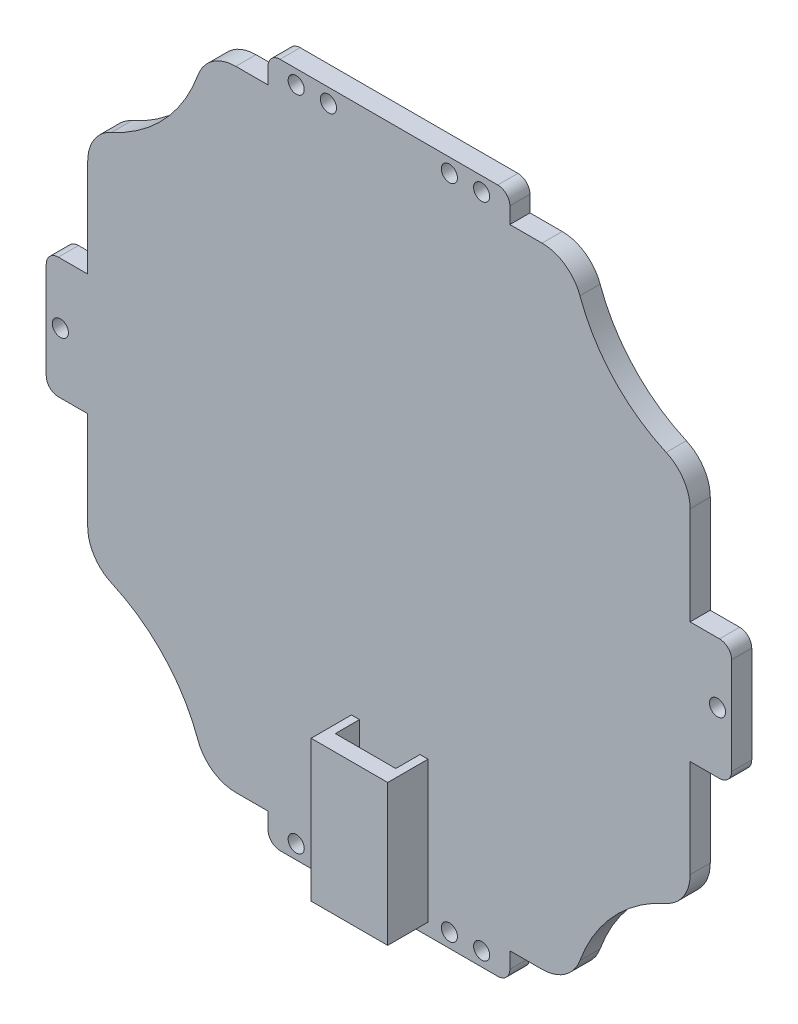
SolidWorks part; units mm, degrees
ref_plane "Front Plane" through (0, 0, 0) normal (0, 0, 1) x (1, 0, 0)
ref_plane "Top Plane" through (0, 0, 0) normal (0, 1, 0) x (1, 0, 0)
ref_plane "Right Plane" through (0, 0, 0) normal (1, 0, 0) x (0, 0, -1)
sketch "Sketch1" plane through (0, 0, 0) normal (0, 0, 1) x (1, 0, 0)
  line L0 (82, 15) -> (74.7088, 15)
  line L1 (-27, -85) -> (27, -85)
  line L2 (-85, -12) -> (-85, 12)
  line L3 (-27, 85) -> (27, 85)
  line L4 (85, -12) -> (85, 12)
  line L5 (30, 82) -> (30, 78)
  line L6 (-85, 85) -> (85, -85) construction
  line L7 (-82, 15) -> (-74.7088, 15)
  line L8 (74.7088, -15) -> (82, -15)
  line L9 (74.7088, 15) -> (74.7088, 39.3024)
  line L10 (74.7088, -15) -> (74.7088, -39.3024)
  line L11 (-74.7088, -15) -> (-82, -15)
  line L12 (-74.7088, 15) -> (-74.7088, 39.3024)
  line L13 (-74.7088, -15) -> (-74.7088, -39.3024)
  line L14 (-30, 82) -> (-30, 78)
  line L15 (30, 78) -> (37.9787, 78)
  line L16 (-30, 78) -> (-37.9787, 78)
  line L17 (30, -78) -> (37.9787, -78)
  line L18 (-30, -82) -> (-30, -78)
  line L19 (30, -82) -> (30, -78)
  line L20 (-30, -78) -> (-37.9787, -78)
  arc A0 (47.383, 71.4) -> (68.7671, 48.4419) centre (85, 85) ccw
  arc A1 (68.7671, -48.4419) -> (47.383, -71.4) centre (85, -85) ccw
  arc A2 (-47.383, -71.4) -> (-68.7671, -48.4419) centre (-85, -85) ccw
  arc A3 (-68.7671, 48.4419) -> (-47.383, 71.4) centre (-85, 85) ccw
  arc A4 (-82, -15) -> (-85, -12) centre (-82, -12) cw
  arc A5 (-85, 12) -> (-82, 15) centre (-82, 12) cw
  arc A6 (-30, -82) -> (-27, -85) centre (-27, -82) ccw
  arc A7 (27, -85) -> (30, -82) centre (27, -82) ccw
  arc A8 (85, -12) -> (82, -15) centre (82, -12) cw
  arc A9 (85, 12) -> (82, 15) centre (82, 12) ccw
  arc A10 (30, 82) -> (27, 85) centre (27, 82) ccw
  arc A11 (-27, 85) -> (-30, 82) centre (-27, 82) ccw
  arc A12 (-37.9787, 78) -> (-47.383, 71.4) centre (-37.9787, 68) ccw
  arc A13 (-68.7671, 48.4419) -> (-74.7088, 39.3024) centre (-64.7088, 39.3024) ccw
  arc A14 (-68.7671, -48.4419) -> (-74.7088, -39.3024) centre (-64.7088, -39.3024) cw
  arc A15 (-37.9787, -78) -> (-47.383, -71.4) centre (-37.9787, -68) cw
  arc A16 (37.9787, -78) -> (47.383, -71.4) centre (37.9787, -68) ccw
  arc A17 (74.7088, -39.3024) -> (68.7671, -48.4419) centre (64.7088, -39.3024) cw
  arc A18 (74.7088, 39.3024) -> (68.7671, 48.4419) centre (64.7088, 39.3024) ccw
  arc A19 (47.383, 71.4) -> (37.9787, 78) centre (37.9787, 68) ccw
  point P0 (0, 0)
  point P6 (-78.3544, -15)
  dimension "D1" = 40
  dimension "D11" = 3
  dimension "D12" = 10
  dimension "D16" = 170
  dimension "D19" = 55
  dimension "D23" = 24.3024
  dimension "D2" = 170
  dimension "D3" = 149.4177
  dimension "D4" = 149.4177
  dimension "D5" = 70
  dimension "D6" = 30
  dimension "D7" = 55
  dimension "D8" = 55
  dimension "D9" = 60
  dimension "D10" = 159.7088
  dimension "D13" = 85
  dimension "D14" = 24
  dimension "D15" = 170
  dimension "D17" = 85
  dimension "D18" = 4
  dimension "D20" = 7
  dimension "D21" = 7
  dimension "D22" = 7
  dimension "D24" = 7.2912
extrude "Boss-Extrude1" add sketch "Sketch1" along normal blind 5
sketch "Sketch2" plane through (0, 0, 0) normal (0, 0, -1) x (-1, 0, 0)
  line L0 (85, 12) -> (85, -12) construction
  line L1 (82, -15) -> (74.7088, -15) construction
  line L2 (-85, -12) -> (-85, 12) construction
  line L3 (30, 82) -> (30, 78) construction
  line L4 (-27, 85) -> (27, 85) construction
  line L5 (-30, 78) -> (-30, 82) construction
  line L6 (-82, 15) -> (-74.7088, 15) construction
  line L7 (30, -78) -> (30, -82) construction
  line L8 (-30, -82) -> (-30, -78) construction
  line L9 (27, -85) -> (-27, -85) construction
  circle A0 centre (81.5, 0) radius 2
  circle A1 centre (-81.5, 0) radius 2
  circle A2 centre (-23, 81.5) radius 2
  circle A3 centre (15, 81.5) radius 2
  circle A4 centre (23, 81.5) radius 2
  circle A5 centre (-15, 81.5) radius 2
  circle A6 centre (-23, -81.5) radius 2
  circle A7 centre (-15, -81.5) radius 2
  circle A8 centre (15, -81.5) radius 2
  circle A9 centre (23, -81.5) radius 2
  dimension "D1" = 4
  dimension "D4" = 4
  dimension "D5" = 4
  dimension "D6" = 4
  dimension "D7" = 4
  dimension "D16" = 4
  dimension "D19" = 4
  dimension "D20" = 4
  dimension "D21" = 4
  dimension "D22" = 4
  dimension "D2" = 3.5
  dimension "D3" = 15
  dimension "D8" = 7
  dimension "D9" = 15
  dimension "D10" = 3.5
  dimension "D11" = 3.5
  dimension "D12" = 15
  dimension "D13" = 7
  dimension "D14" = 3.5
  dimension "D15" = 3.5
  dimension "D17" = 3.5
  dimension "D18" = 15
  dimension "D23" = 7
  dimension "D24" = 15
  dimension "D25" = 7
  dimension "D26" = 15
  dimension "D27" = 3.5
  dimension "D28" = 3.5
  dimension "D29" = 3.5
  dimension "D30" = 3.5
extrude "Cut-Extrude1" cut sketch "Sketch2" against normal blind 5
sketch "Sketch3" plane through (0, 0, 0) normal (0, 0, -1) x (-1, 0, 0)
  line L12 (-30, -70) -> (-45, -44.0192)
  line L13 (30, -70) -> (-30, -70)
  line L14 (45, -44.0192) -> (30, -70)
  line L15 (-45, -44.0192) -> (45, -44.0192)
  line L16 (65, 45) -> (-65, 45)
  line L17 (45, 10.359) -> (65, 45)
  line L18 (-45, 10.359) -> (45, 10.359)
  line L19 (-65, 45) -> (-45, 10.359)
extrude "Cut-Extrude2" cut sketch "Sketch3" against normal blind 3
sketch "Sketch4" plane through (0, 0, 5) normal (0, 0, 1) x (1, 0, 0)
  line L0 (-27, -85) -> (27, -85) construction
  line L1 (-9.3, -47) -> (9.7, -47)
  line L2 (-9.3, -47) -> (-9.3, -82)
  line L3 (-9.3, -82) -> (9.7, -82)
  line L4 (9.7, -47) -> (9.7, -82)
  line L5 (-85, 12) -> (-85, -12) construction
  dimension "D1" = 19
  dimension "D2" = 35
  dimension "D3" = 3
  dimension "D4" = 75.7
extrude "Boss-Extrude2" add sketch "Sketch4" along normal blind 10
sketch "Sketch6" plane through (0, -82, 0) normal (0, -1, 0) x (1, 0, 0)
  line L0 (9.7, 15) -> (9.7, 5) construction
  line L1 (-7.3, 13) -> (7.7, 13)
  line L2 (-7.3, 13) -> (-7.3, 5)
  line L3 (-7.3, 5) -> (7.7, 5)
  line L4 (7.7, 13) -> (7.7, 5)
  line L5 (-9.3, 15) -> (-9.3, 5) construction
  line L6 (-9.3, 5) -> (9.7, 5) construction
  line L7 (-9.3, 15) -> (9.7, 15) construction
  dimension "D1" = 2
  dimension "D2" = 2
  dimension "D3" = 0
  dimension "D4" = 2
extrude "Cut-Extrude4" cut sketch "Sketch6" against normal blind 33
sketch "Sketch7" plane through (0, -47, 0) normal (0, 1, 0) x (1, 0, 0)
  line L0 (9.7, -15) -> (9.7, -5) construction
  line L1 (-7.3, -5) -> (7.7, -5)
  line L2 (-7.3, -5) -> (-7.3, -11)
  line L3 (-7.3, -11) -> (7.7, -11)
  line L4 (7.7, -5) -> (7.7, -11)
  line L5 (-9.3, -15) -> (-9.3, -5) construction
  line L6 (9.7, -5) -> (-9.3, -5) construction
  line L7 (9.7, -15) -> (-9.3, -15) construction
  dimension "D1" = 2
  dimension "D2" = 2
  dimension "D3" = 0
  dimension "D4" = 4
extrude "Cut-Extrude5" cut sketch "Sketch7" against normal blind 2
